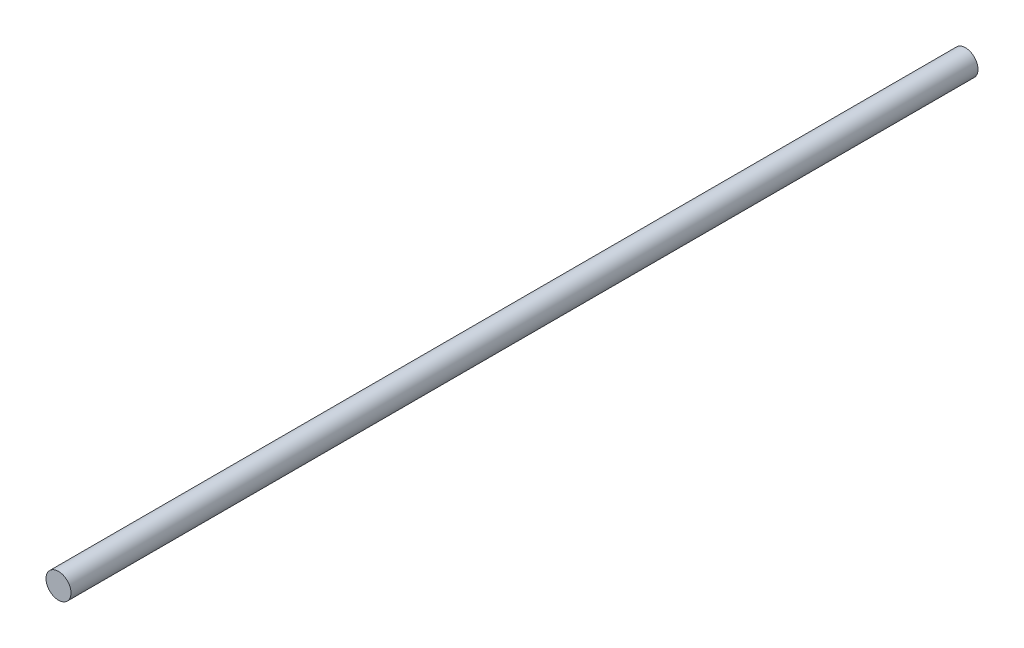
SolidWorks part; units mm, degrees
ref_plane "Front Plane" through (0, 0, 0) normal (0, 0, 1) x (1, 0, 0)
ref_plane "Top Plane" through (0, 0, 0) normal (0, 1, 0) x (1, 0, 0)
ref_plane "Right Plane" through (0, 0, 0) normal (1, 0, 0) x (0, 0, -1)
sketch "Sketch1" plane through (0, 0, 0) normal (0, 0, 1) x (1, 0, 0)
  line L1 (-4, 0) -> (4, 0) construction
  dimension "OD" = 8
sketch "Sketch2" plane through (0, 0, 0) normal (1, 0, 0) x (0, 0, -1)
  line L0 (152.4, 0) -> (-152.4, 0)
  point P4 (0, 0)
  dimension "Length" = 304.8
sketch "Sketch3" plane through (0, 0, 0) normal (0, 0, 1) x (1, 0, 0)
  circle A0 centre (0, 0) radius 4
extrude "Boss-Extrude1" add sketch "Sketch3" along normal mid plane 290
